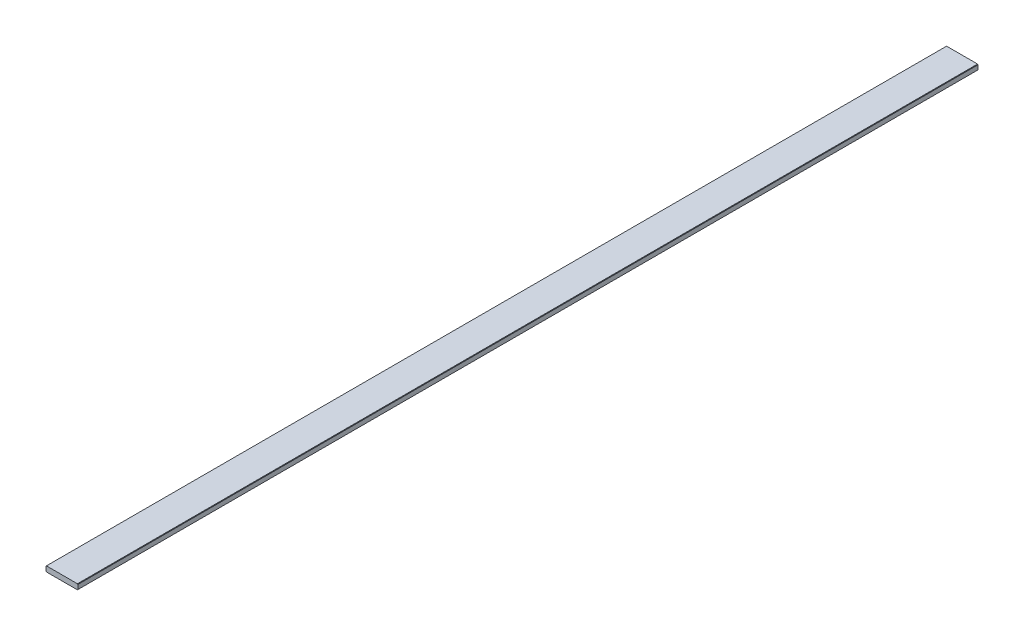
SolidWorks part; units mm, degrees
ref_plane "Спереди" through (0, 0, 0) normal (0, 0, 1) x (1, 0, 0)
ref_plane "Сверху" through (0, 0, 0) normal (0, 1, 0) x (1, 0, 0)
ref_plane "Справа" through (0, 0, 0) normal (1, 0, 0) x (0, 0, -1)
sketch "Эскиз1" plane through (0, 0, 0) normal (0, 0, 1) x (1, 0, 0)
  line L0 (-75, 10.5) -> (-73, 12.5)
  line L1 (-73, 12.5) -> (73, 12.5)
  line L2 (-75, 10.5) -> (-75, -10.5)
  line L3 (-73, -12.5) -> (73, -12.5)
  line L4 (75, 10.5) -> (75, -10.5)
  line L5 (-75, 12.5) -> (75, -12.5) construction
  line L6 (-75, -12.5) -> (75, 12.5) construction
  line L7 (-75, -10.5) -> (-73, -12.5)
  line L8 (73, -12.5) -> (75, -10.5)
  line L9 (73, 12.5) -> (75, 10.5)
  point P0 (0, 0)
  dimension "D1" = 150
  dimension "D2" = 25
extrude "Бобышка-Вытянуть1" add sketch "Эскиз1" along normal blind 4240
